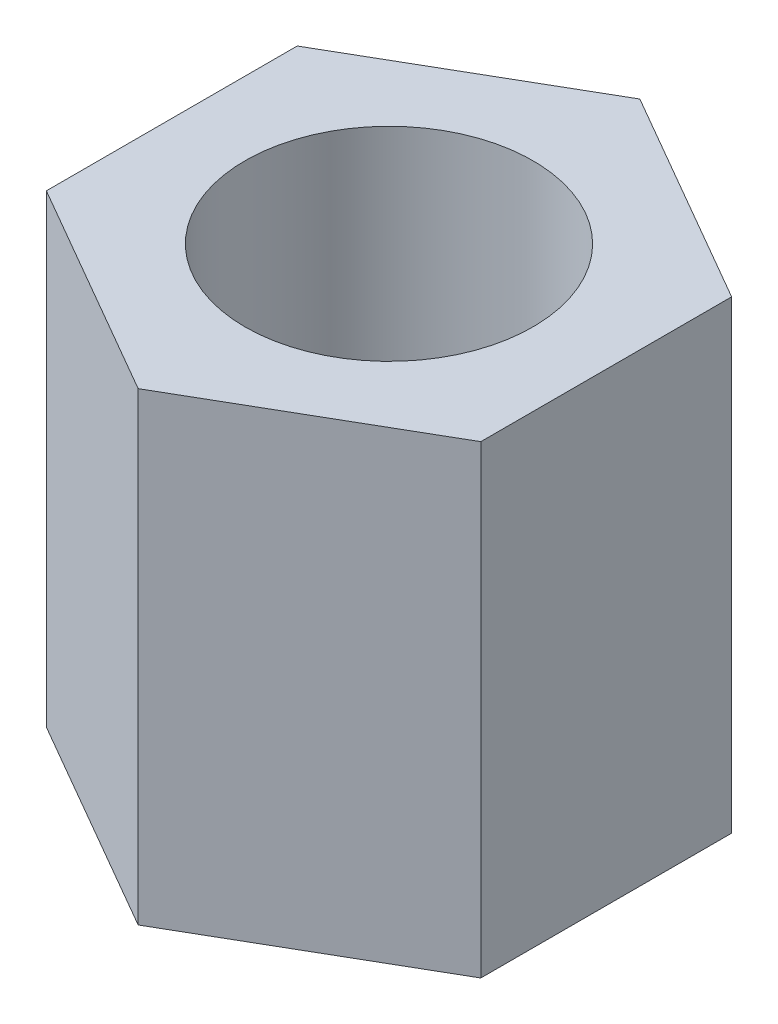
SolidWorks part; units mm, degrees
ref_plane "前视基准面" through (0, 0, 0) normal (0, 0, 1) x (1, 0, 0)
ref_plane "上视基准面" through (0, 0, 0) normal (0, 1, 0) x (1, 0, 0)
ref_plane "右视基准面" through (0, 0, 0) normal (1, 0, 0) x (0, 0, -1)
sketch "草图1" plane through (0, 0, 0) normal (0, 1, 0) x (1, 0, 0)
  line L1 (0, 2.7) -> (-2.3383, 1.35)
  line L2 (-2.3383, 1.35) -> (-2.3383, -1.35)
  line L3 (-2.3383, -1.35) -> (0, -2.7)
  line L4 (0, -2.7) -> (2.3383, -1.35)
  line L5 (2.3383, -1.35) -> (2.3383, 1.35)
  line L6 (2.3383, 1.35) -> (0, 2.7)
  circle A0 centre (0, 0) radius 2.7 construction
  circle A1 centre (0, 0) radius 1.55
  dimension "D1" = 3.1
extrude "凸台-拉伸1" add sketch "草图1" along normal blind 5
